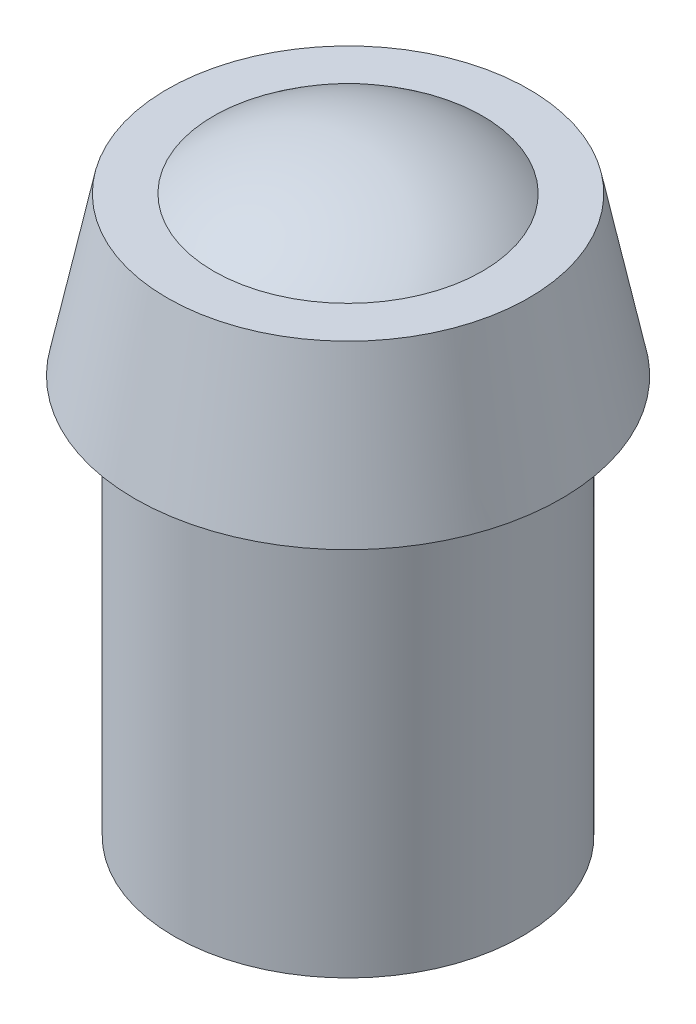
SolidWorks part; units mm, degrees
ref_plane "Front Plane" through (0, 0, 0) normal (0, 0, 1) x (1, 0, 0)
ref_plane "Top Plane" through (0, 0, 0) normal (0, 1, 0) x (1, 0, 0)
ref_plane "Right Plane" through (0, 0, 0) normal (1, 0, 0) x (0, 0, -1)
sketch "Sketch1" plane through (0, 0, 0) normal (0, 0, 1) x (1, 0, 0)
  line L0 (0, 0) -> (0, -12) construction
  line L1 (0, 0) -> (3.9, 0)
  line L2 (3.9, 0) -> (4.6, -3.4)
  line L3 (4.6, -3.4) -> (3.75, -3.4)
  line L4 (3.75, -3.4) -> (3.75, -12)
  line L5 (3.75, -12) -> (0, -12)
  line L6 (0, 0) -> (0, -12)
  dimension "D1" = 12
  dimension "D2" = 7.8
  dimension "D3" = 9.2
  dimension "D4" = 8.6
  dimension "D5" = 7.5
revolve "Revolve1" add sketch "Sketch1" angle 360 about L0
sketch "Sketch2" plane through (0, 0, 0) normal (0, 0, 1) x (1, 0, 0)
  line L0 (3.9, 0) -> (-3.9, 0) construction
  line L1 (0, -3.4) -> (0, 0) construction
  line L2 (0, 1) -> (0, 0)
  line L3 (0, 0) -> (-2.9, 0)
  arc A0 (-2.9, 0) -> (0, 1) centre (0, -3.705) cw
  dimension "D1" = 1
  dimension "D2" = 1
revolve "Revolve2" add sketch "Sketch2" angle 360 about L2
